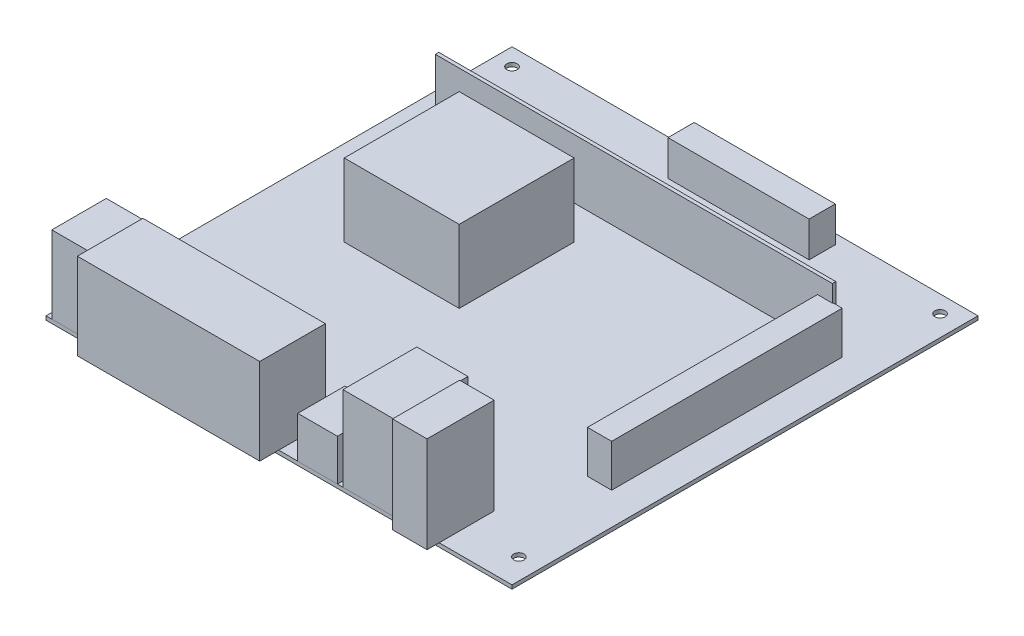
SolidWorks part; units mm, degrees
ref_plane "Front Plane" through (0, 0, 0) normal (0, 0, 1) x (1, 0, 0)
ref_plane "Top Plane" through (0, 0, 0) normal (0, 1, 0) x (1, 0, 0)
ref_plane "Right Plane" through (0, 0, 0) normal (1, 0, 0) x (0, 0, -1)
sketch "Sketch1" plane through (0, 0, 0) normal (0, 1, 0) x (1, 0, 0)
  line L0 (0, -55) -> (0, 55) construction
  line L1 (-85.725, 85.725) -> (85.725, 85.725)
  line L2 (-85.725, 85.725) -> (-85.725, -85.725)
  line L3 (-85.725, -85.725) -> (85.725, -85.725)
  line L4 (85.725, 85.725) -> (85.725, -85.725)
  line L5 (-55, 0) -> (55, 0) construction
  point P4 (0, 85.725)
  point P7 (-85.725, 0)
  dimension "D1" = 171.45
extrude "PCB" add sketch "Sketch1" along normal blind 1.397
sketch "Sketch2" plane through (0, 1.397, 0) normal (0, 1, 0) x (1, 0, 0)
  line L0 (-85.725, -85.725) -> (85.725, -85.725) construction
  line L1 (-83.5914, -85.725) -> (-69.2912, -85.725)
  line L2 (-83.5914, -85.725) -> (-83.5914, -65.6844)
  line L3 (-83.5914, -65.6844) -> (-69.2912, -65.6844)
  line L4 (-69.2912, -85.725) -> (-69.2912, -65.6844)
  line L5 (-85.725, 85.725) -> (-85.725, -85.725) construction
  dimension "D1" = 20.0406
  dimension "D2" = 14.3002
  dimension "D3" = 2.1336
extrude "PS2" add sketch "Sketch2" along normal blind 28.448 separate body
sketch "Sketch3" plane through (0, 1.397, 0) normal (0, 1, 0) x (1, 0, 0)
  line L0 (-69.2912, -85.725) -> (-69.2912, -65.6844) construction
  line L1 (-67.2084, -92.71) -> (-0.1016, -92.71)
  line L2 (-67.2084, -92.71) -> (-67.2084, -68.58)
  line L3 (-67.2084, -68.58) -> (-0.1016, -68.58)
  line L4 (-0.1016, -92.71) -> (-0.1016, -68.58)
  line L5 (-85.725, -85.725) -> (85.725, -85.725) construction
  dimension "D1" = 67.1068
  dimension "D2" = 2.0828
  dimension "D3" = 24.13
  dimension "D4" = 6.985
extrude "VGA" add sketch "Sketch3" along normal blind 31.75 separate body
sketch "Sketch4" plane through (0, 1.397, 0) normal (0, 1, 0) x (1, 0, 0)
  line L0 (-85.725, -85.725) -> (85.725, -85.725) construction
  line L1 (6.8929, -85.725) -> (21.4979, -85.725)
  line L2 (6.8929, -85.725) -> (6.8929, -68.3768)
  line L3 (6.8929, -68.3768) -> (21.4979, -68.3768)
  line L4 (21.4979, -85.725) -> (21.4979, -68.3768)
  dimension "D1" = 14.605
  dimension "D2" = 17.3482
extrude "USB" add sketch "Sketch4" along normal blind 15.24 separate body
sketch "Sketch5" plane through (0, 1.397, 0) normal (0, 1, 0) x (1, 0, 0)
  line L0 (-85.725, -85.725) -> (85.725, -85.725) construction
  line L1 (23.5299, -85.725) -> (42.3259, -85.725)
  line L2 (23.5299, -85.725) -> (23.5299, -58.547)
  line L3 (23.5299, -58.547) -> (42.3259, -58.547)
  line L4 (42.3259, -85.725) -> (42.3259, -58.547)
  line L5 (21.4979, -85.725) -> (21.4979, -68.3768) construction
  dimension "D1" = 18.796
  dimension "D2" = 27.178
  dimension "D3" = 2.032
extrude "EthernetUSB" add sketch "Sketch5" along normal blind 31.115 separate body
sketch "Sketch6" plane through (0, 1.397, 0) normal (0, 1, 0) x (-1, 0, 0)
  line L1 (-46.2121, 90.17) -> (-58.9121, 90.17)
  line L2 (-46.2121, 90.17) -> (-46.2121, 65.4812)
  line L3 (-46.2121, 65.4812) -> (-58.9121, 65.4812)
  line L4 (-58.9121, 90.17) -> (-58.9121, 65.4812)
  line L5 (-42.3259, 85.725) -> (-42.3259, 58.547) construction
  line L6 (85.725, 85.725) -> (-85.725, 85.725) construction
  dimension "D1" = 12.7
  dimension "D2" = 24.6888
  dimension "D3" = 3.8862
  dimension "D4" = 4.445
extrude "Audio" add sketch "Sketch6" along normal blind 35.3314 separate body
sketch "Sketch7" plane through (0, 1.397, 0) normal (0, 1, 0) x (1, 0, 0)
  line L0 (-85.725, 85.725) -> (-85.725, -85.725) construction
  line L1 (-54.356, 34.925) -> (-12.065, 34.925)
  line L2 (-54.356, 34.925) -> (-54.356, -7.366)
  line L3 (-54.356, -7.366) -> (-12.065, -7.366)
  line L4 (-12.065, 34.925) -> (-12.065, -7.366)
  line L5 (85.725, 85.725) -> (-85.725, 85.725) construction
  dimension "D1" = 42.291
  dimension "D2" = 31.369
  dimension "D3" = 50.8
extrude "Heatsink" add sketch "Sketch7" along normal blind 26.797 separate body
sketch "Sketch8" plane through (0, 1.397, 0) normal (0, 1, 0) x (1, 0, 0)
  line L1 (65.0188, 47.5827) -> (73.9088, 47.5827)
  line L2 (65.0188, 47.5827) -> (65.0188, -37.2533)
  line L3 (65.0188, -37.2533) -> (73.9088, -37.2533)
  line L4 (73.9088, 47.5827) -> (73.9088, -37.2533)
  dimension "D1" = 84.836
  dimension "D2" = 8.89
extrude "Boss-Extrude8" add sketch "Sketch8" along normal blind 15.5956 separate body
sketch "Sketch9" plane through (0, 1.397, 0) normal (0, 1, 0) x (1, 0, 0)
  line L0 (85.725, 85.725) -> (-85.725, 85.725) construction
  line L1 (-15.0876, 82.1182) -> (36.83, 82.1182)
  line L2 (-15.0876, 82.1182) -> (-15.0876, 72.4662)
  line L3 (-15.0876, 72.4662) -> (36.83, 72.4662)
  line L4 (36.83, 82.1182) -> (36.83, 72.4662)
  line L5 (85.725, -85.725) -> (85.725, 85.725) construction
  dimension "D1" = 51.9176
  dimension "D2" = 9.652
  dimension "D3" = 3.6068
  dimension "D4" = 48.895
extrude "Boss-Extrude9" add sketch "Sketch9" along normal blind 13.0048 separate body
sketch "Sketch10" plane through (0, 1.397, 0) normal (0, 1, 0) x (1, 0, 0)
  line L0 (85.725, 85.725) -> (-85.725, 85.725) construction
  line L1 (85.725, -85.725) -> (85.725, 85.725) construction
  line L2 (-85.725, 85.725) -> (-85.725, -85.725) construction
  line L3 (-85.725, -85.725) -> (85.725, -85.725) construction
  circle A0 centre (-79.375, 79.375) radius 1.905
  circle A1 centre (78.105, 79.375) radius 1.905
  circle A2 centre (78.105, -75.565) radius 1.905
  circle A3 centre (-79.375, -52.705) radius 1.905
  dimension "D1" = 3.81
  dimension "D2" = 6.35
  dimension "D3" = 7.62
  dimension "D4" = 6.35
  dimension "D5" = 6.35
  dimension "D6" = 7.62
  dimension "D7" = 10.16
  dimension "D8" = 6.35
  dimension "D9" = 33.02
extrude "Holes" cut sketch "Sketch10" against normal through all
sketch "Sketch11" plane through (0, 1.397, 0) normal (0, 1, 0) x (1, 0, 0)
  line L0 (-85.725, 85.725) -> (-85.725, -85.725) construction
  line L1 (85.725, 85.725) -> (-85.725, 85.725) construction
  line L5 (-75.565, 48.641) -> (70.485, 48.641)
  line L6 (-75.565, 48.641) -> (-75.565, 47.371)
  line L7 (-75.565, 47.371) -> (70.485, 47.371)
  line L8 (70.485, 48.641) -> (70.485, 47.371)
  dimension "D1" = 1.27
  dimension "D2" = 146.05
  dimension "D3" = 10.16
  dimension "D4" = 37.084
extrude "RAM" add sketch "Sketch11" along normal blind 21.844 separate body
